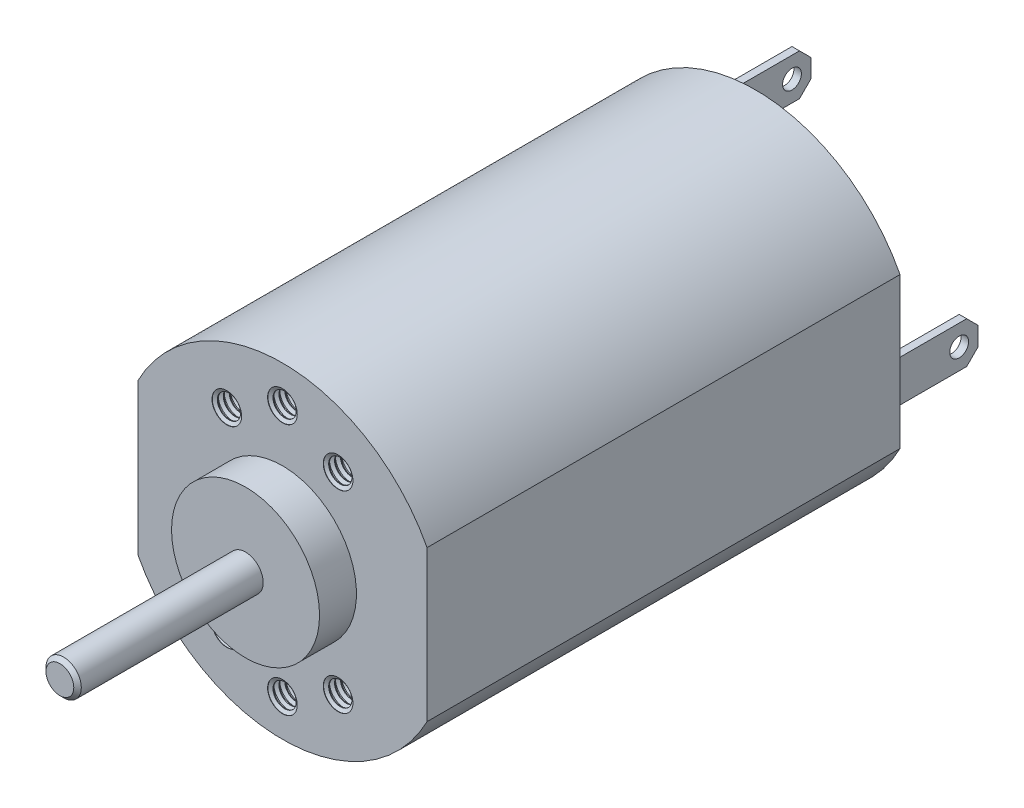
SolidWorks part; units mm, degrees
ref_plane "Front" through (0, 0, 0) normal (0, 0, 1) x (1, 0, 0)
ref_plane "Top" through (0, 0, 0) normal (0, 1, 0) x (1, 0, 0)
ref_plane "Right" through (0, 0, 0) normal (1, 0, 0) x (0, 0, -1)
sketch "Sketch1" plane through (0, 0, 0) normal (0, 0, 1) x (1, 0, 0)
  circle A0 centre (0, 0) radius 4.9911
  dimension "D1" = 9.9822
extrude "Extrude1" add sketch "Sketch1" along normal blind 2.4892
sketch "Sketch2" plane through (0, 0, 0) normal (0, 0, -1) x (-1, 0, 0)
  line L0 (-9.7536, 5.0821) -> (-9.7536, -5.0821)
  line L1 (9.7536, 5.0821) -> (9.7536, -5.0821)
  line L2 (0, 2.306) -> (0, -1.5823) construction
  arc A0 (-9.7536, -5.0821) -> (9.7536, -5.0821) centre (0, 0) ccw
  circle A1 centre (0, 0) radius 4.9911 construction
  arc A2 (9.7536, 5.0821) -> (-9.7536, 5.0821) centre (0, 0) ccw
  dimension "D1" = 21.9964
  dimension "D2" = 19.5072
extrude "Extrude2" add sketch "Sketch2" along normal blind 31.9024
sketch "Sketch3" plane through (0, 0, 0) normal (0, 0, 1) x (1, 0, 0)
  circle A0 centre (0, 0) radius 1.1906
  circle A1 centre (0, 0) radius 4.9911 construction
  dimension "D1" = 2.3813
extrude "Extrude3" add sketch "Sketch3" along normal blind 15.0114
sketch "Sketch4" plane through (0, 0, -31.9024) normal (0, 0, -1) x (-1, 0, 0)
  line L1 (5.3848, 6.4008) -> (5.8928, 6.4008)
  line L2 (5.3848, 6.4008) -> (5.3848, 3.6068)
  line L3 (5.3848, 3.6068) -> (5.8928, 3.6068)
  line L4 (5.8928, 6.4008) -> (5.8928, 3.6068)
  point P4 (5.6388, 6.4008)
  point P5 (5.8928, 5.0038)
  dimension "D1" = 5.6388
  dimension "D2" = 5.0038
  dimension "D3" = 2.794
  dimension "D4" = 0.508
extrude "Extrude4" add sketch "Sketch4" along normal blind 9.1186
sketch "Sketch5" plane through (-5.3848, 0, 0) normal (1, 0, 0) x (0, 0, -1)
  line L0 (40.259, 6.4008) -> (41.021, 6.4008)
  line L1 (41.021, 6.4008) -> (41.021, 5.6388)
  line L2 (41.021, 5.6388) -> (40.259, 6.4008)
  line L3 (41.021, 6.4008) -> (41.021, 3.6068) construction
  line L4 (40.259, 3.6068) -> (41.021, 3.6068)
  line L5 (41.021, 3.6068) -> (41.021, 4.3688)
  line L6 (41.021, 4.3688) -> (40.259, 3.6068)
  line L7 (41.021, 3.6068) -> (31.9024, 3.6068) construction
  line L8 (41.021, 6.4008) -> (31.9024, 6.4008) construction
  line L9 (39.751, 5.0038) -> (41.021, 5.0038) construction
  circle A0 centre (39.751, 5.0038) radius 0.635
  dimension "D3" = 1.27
  dimension "D4" = 1.27
  dimension "D1" = 45
  dimension "D2" = 0.762
extrude "Cut-Extrude1" cut sketch "Sketch5" against normal through all
pattern_linear "LPattern1" count 2 spacing 11.2776 along (1, 0, 0) count 2 spacing 10.0076 along (0, -1, 0) skipping (0, 1), (1, 0) of "Extrude4", "Cut-Extrude1"
sketch "Sketch7" plane through (0, 0, 0) normal (1, 0, 0) x (0, 0, -1)
  line L0 (-15.8213, 0) -> (8.2348, 0) construction
  line L1 (-2.3939, 8.4963) -> (3.8072, 8.4963) construction
  line L2 (-0.2028, 8.4963) -> (2.9972, 8.4963)
  line L3 (2.9972, 8.4963) -> (2.9972, 9.2798)
  line L4 (2.9972, 9.2798) -> (2.9472, 9.2798)
  line L5 (2.9472, 9.2798) -> (2.8222, 9.4963)
  line L6 (2.8222, 9.4963) -> (2.7222, 9.4963)
  line L7 (2.7222, 9.4963) -> (2.5972, 9.2798)
  line L8 (2.5972, 9.2798) -> (2.9472, 9.2798) construction
  line L9 (2.7722, 9.2798) -> (2.7722, 9.4963) construction
  line L10 (0, 10.9982) -> (0, 5.0821) construction
  line L11 (2.3222, 9.4963) -> (2.1972, 9.2798)
  line L12 (2.4222, 9.4963) -> (2.3222, 9.4963)
  line L13 (2.5472, 9.2798) -> (2.4222, 9.4963)
  line L14 (2.5972, 9.2798) -> (2.5472, 9.2798)
  line L15 (1.9222, 9.4963) -> (1.7972, 9.2798)
  line L16 (2.0222, 9.4963) -> (1.9222, 9.4963)
  line L17 (2.1472, 9.2798) -> (2.0222, 9.4963)
  line L18 (2.1972, 9.2798) -> (2.1472, 9.2798)
  line L19 (1.5222, 9.4963) -> (1.3972, 9.2798)
  line L20 (1.6222, 9.4963) -> (1.5222, 9.4963)
  line L21 (1.7472, 9.2798) -> (1.6222, 9.4963)
  line L22 (1.7972, 9.2798) -> (1.7472, 9.2798)
  line L23 (1.1222, 9.4963) -> (0.9972, 9.2798)
  line L24 (1.2222, 9.4963) -> (1.1222, 9.4963)
  line L25 (1.3472, 9.2798) -> (1.2222, 9.4963)
  line L26 (1.3972, 9.2798) -> (1.3472, 9.2798)
  line L27 (0.7222, 9.4963) -> (0.5972, 9.2798)
  line L28 (0.8222, 9.4963) -> (0.7222, 9.4963)
  line L29 (0.9472, 9.2798) -> (0.8222, 9.4963)
  line L30 (0.9972, 9.2798) -> (0.9472, 9.2798)
  line L31 (0.3222, 9.4963) -> (0.1972, 9.2798)
  line L32 (0.4222, 9.4963) -> (0.3222, 9.4963)
  line L33 (0.5472, 9.2798) -> (0.4222, 9.4963)
  line L34 (0.5972, 9.2798) -> (0.5472, 9.2798)
  line L35 (-0.0778, 9.4963) -> (-0.2028, 9.2798)
  line L36 (0.0222, 9.4963) -> (-0.0778, 9.4963)
  line L37 (0.1472, 9.2798) -> (0.0222, 9.4963)
  line L38 (0.1972, 9.2798) -> (0.1472, 9.2798)
  line L39 (-0.2028, 9.2798) -> (-0.2028, 8.4963)
  dimension "D1" = 16.9926
  dimension "D2" = 2
  dimension "D3" = 0.4
  dimension "D4" = 60
  dimension "D5" = 0.05
  dimension "D6" = 0.1
  dimension "D7" = 2.9972
revolve "Cut-Revolve1" cut sketch "Sketch7" angle 360 about L1
pattern_circular "CirPattern1" count 2 over 360 about axis through (0, 0, 0) along (0, 0, 1) of "Cut-Revolve1"
ref_plane "Plane1" through (0, 0, 0) normal (0.866, -0.5, 0) x (0, 0, -1)
sketch "Sketch8" plane through (0, 0, 0) normal (0.866, -0.5, 0) x (0, 0, -1)
  line L0 (-16.142, 0) -> (10.2662, 0) construction
  line L1 (-3.687, 7.5057) -> (4.408, 7.5057) construction
  line L2 (-0.2028, 7.5057) -> (2.9972, 7.5057)
  line L3 (2.9972, 7.5057) -> (2.9972, 8.2892)
  line L4 (2.9972, 8.2892) -> (2.9472, 8.2892)
  line L5 (2.9472, 8.2892) -> (2.8222, 8.5057)
  line L6 (2.8222, 8.5057) -> (2.7222, 8.5057)
  line L7 (2.7222, 8.5057) -> (2.5972, 8.2892)
  line L8 (2.5972, 8.2892) -> (2.9472, 8.2892) construction
  line L9 (2.7722, 8.5057) -> (2.7722, 8.2892) construction
  line L10 (0, 9.278) -> (0, 0.4756) construction
  line L11 (2.3222, 8.5057) -> (2.1972, 8.2892)
  line L12 (2.4222, 8.5057) -> (2.3222, 8.5057)
  line L13 (2.5472, 8.2892) -> (2.4222, 8.5057)
  line L14 (2.5972, 8.2892) -> (2.5472, 8.2892)
  line L15 (1.9222, 8.5057) -> (1.7972, 8.2892)
  line L16 (2.0222, 8.5057) -> (1.9222, 8.5057)
  line L17 (2.1472, 8.2892) -> (2.0222, 8.5057)
  line L18 (2.1972, 8.2892) -> (2.1472, 8.2892)
  line L19 (1.5222, 8.5057) -> (1.3972, 8.2892)
  line L20 (1.6222, 8.5057) -> (1.5222, 8.5057)
  line L21 (1.7472, 8.2892) -> (1.6222, 8.5057)
  line L22 (1.7972, 8.2892) -> (1.7472, 8.2892)
  line L23 (1.1222, 8.5057) -> (0.9972, 8.2892)
  line L24 (1.2222, 8.5057) -> (1.1222, 8.5057)
  line L25 (1.3472, 8.2892) -> (1.2222, 8.5057)
  line L26 (1.3972, 8.2892) -> (1.3472, 8.2892)
  line L27 (0.7222, 8.5057) -> (0.5972, 8.2892)
  line L28 (0.8222, 8.5057) -> (0.7222, 8.5057)
  line L29 (0.9472, 8.2892) -> (0.8222, 8.5057)
  line L30 (0.9972, 8.2892) -> (0.9472, 8.2892)
  line L31 (0.3222, 8.5057) -> (0.1972, 8.2892)
  line L32 (0.4222, 8.5057) -> (0.3222, 8.5057)
  line L33 (0.5472, 8.2892) -> (0.4222, 8.5057)
  line L34 (0.5972, 8.2892) -> (0.5472, 8.2892)
  line L35 (-0.0778, 8.5057) -> (-0.2028, 8.2892)
  line L36 (0.0222, 8.5057) -> (-0.0778, 8.5057)
  line L37 (0.1472, 8.2892) -> (0.0222, 8.5057)
  line L38 (0.1972, 8.2892) -> (0.1472, 8.2892)
  line L39 (-0.2028, 8.2892) -> (-0.2028, 7.5057)
  dimension "D1" = 15.0114
  dimension "D2" = 2
  dimension "D3" = 60
  dimension "D4" = 0.4
  dimension "D5" = 0.05
  dimension "D6" = 0.1
  dimension "D7" = 2.9972
revolve "Cut-Revolve2" cut sketch "Sketch8" angle 360 about L1
pattern_circular "CirPattern2" count 6 over 360 about axis through (0, 0, 0) along (0, 0, 1) skipping 2, 5 of "Cut-Revolve2"
chamfer "Chamfer1" distance 0.254 angle 45 1 edges at (1.1906, 0, 15.0114)
